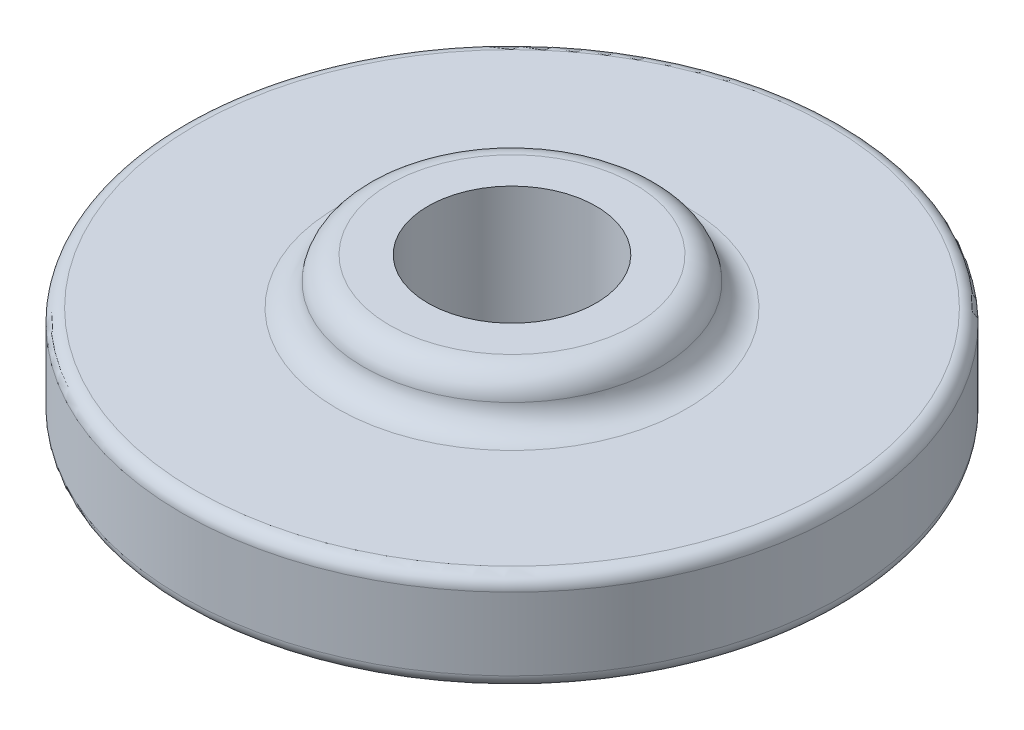
SolidWorks part; units mm, degrees
ref_plane "Front Plane" through (0, 0, 0) normal (0, 0, 1) x (1, 0, 0)
ref_plane "Top Plane" through (0, 0, 0) normal (0, 1, 0) x (1, 0, 0)
ref_plane "Right Plane" through (0, 0, 0) normal (1, 0, 0) x (0, 0, -1)
sketch "Sketch1" plane through (0, 0, 0) normal (0, 1, 0) x (1, 0, 0)
  circle A0 centre (0, 0) radius 10
  dimension "D1" = 20
extrude "Boss-Extrude1" add sketch "Sketch1" along normal blind 3
sketch "Sketch2" plane through (0, 3, 0) normal (0, 1, 0) x (1, 0, 0)
  circle A0 centre (0, 0) radius 2.55
  dimension "D1" = 5.1
extrude "Cut-Extrude1" cut sketch "Sketch2" against normal blind 2.6
fillet "Fillet1" radius 0.4 2 edges at (0, 0, 10) (0, 3, 10)
sketch "Sketch3" plane through (0, 3, 0) normal (0, 1, 0) x (1, 0, 0)
  circle A0 centre (0, 0) radius 2.55
  circle A1 centre (0, 0) radius 4.5
  dimension "D1" = 9
extrude "Boss-Extrude2" add sketch "Sketch3" along normal blind 1.4
fillet "Fillet2" radius 0.8 1 edges at (0, 3, 4.5)
fillet "Fillet3" radius 0.8 1 edges at (0, 4.4, 4.5)
